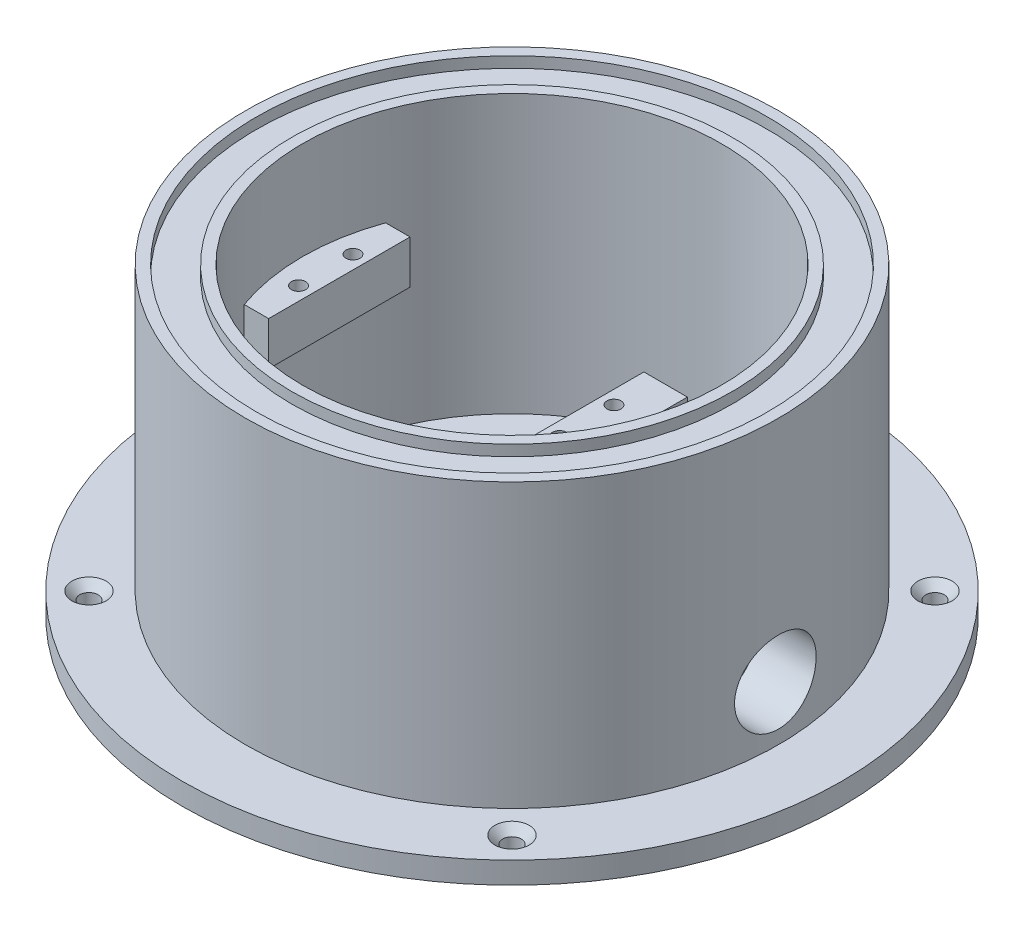
SolidWorks part; units mm, degrees
ref_plane "Front Plane" through (0, 0, 0) normal (0, 0, 1) x (1, 0, 0)
ref_plane "Top Plane" through (0, 0, 0) normal (0, 1, 0) x (1, 0, 0)
ref_plane "Right Plane" through (0, 0, 0) normal (1, 0, 0) x (0, 0, -1)
sketch "Sketch1" plane through (0, 0, 0) normal (0, 1, 0) x (1, 0, 0)
  circle A0 centre (0, 0) radius 60.625
  circle A1 centre (0, 0) radius 45
  dimension "D1" = 121.25
  dimension "D2" = 90
extrude "Boss-Extrude1" add sketch "Sketch1" along normal blind 4 contours A0
sketch "Sketch2" plane through (0, 4, 0) normal (0, 1, 0) x (1, 0, 0)
  circle A0 centre (0, 0) radius 45 construction
  circle A1 centre (0, 0) radius 45
  circle A2 centre (0, 0) radius 49
  dimension "D1" = 4
extrude "Boss-Extrude2" add sketch "Sketch2" along normal blind 52
ref_plane "Plane1" through (0, 36, 0) normal (0, 1, 0) x (1, 0, 0)
sketch "Sketch4" plane through (0, 0, 0) normal (0, 0, 1) x (1, 0, 0)
  line L0 (-60.625, 0) -> (60.625, 0) construction
  line L1 (11.25, 38) -> (19.25, 38)
  line L2 (11.25, 38) -> (11.25, 0)
  line L3 (11.25, 0) -> (19.25, 0)
  line L4 (19.25, 38) -> (19.25, 0)
  line L5 (49, 56) -> (-49, 56) construction
  line L6 (-45, 56) -> (-45, 4)
  line L7 (-31.75, 38) -> (-46.75, 38)
  line L8 (-31.75, 38) -> (-31.75, 30)
  line L9 (-31.75, 30) -> (-46.75, 30)
  line L10 (-46.75, 38) -> (-46.75, 30)
  line L11 (60.625, 4) -> (-60.625, 4) construction
  line L12 (-31.75, 30) -> (-45, 16.75)
  dimension "D1" = 11.25
  dimension "D2" = 8
  dimension "D3" = 18
  dimension "D4" = 43
  dimension "D5" = 15
  dimension "D6" = 8
  dimension "D7" = 45
  dimension "D8" = 18
extrude "Boss-Extrude4" add sketch "Sketch4" along normal mid plane 26 contours L9 L8 L7 L6 | L12 L9 L6 | L1 L4 L3 L2
sketch "Sketch5" plane through (0, 0, 0) normal (0, -1, 0) x (1, 0, 0)
  line L0 (11.25, 13) -> (29.0674, 34.3524)
  line L1 (11.25, -13) -> (29.0674, -34.3524)
  line L2 (11.25, 13) -> (11.25, -13)
  circle A0 centre (0, 0) radius 45 construction
  arc A1 (29.0674, -34.3524) -> (29.0674, 34.3524) centre (0, 0) ccw
extrude "Boss-Extrude5" add sketch "Sketch5" against normal up to surface (4 mm away) contours L0 A1 L1 L2 up to face at (0, 4, 60.625)
sketch "Sketch18" plane through (0, 56, 0) normal (0, 1, 0) x (1, 0, 0)
  circle A0 centre (0, 0) radius 38.5
  circle A1 centre (0, 0) radius 45.1137
extrude "Boss-Extrude6" add sketch "Sketch18" against normal up to surface (56 mm away) from offset 0 up to face at (0, 0, 60.625)
sketch "Sketch7" plane through (0, 38, 0) normal (0, 1, 0) x (1, 0, 0)
  line L0 (-31.75, -13) -> (-31.75, 13) construction
  circle A0 centre (-34.25, 5) radius 1.3
  circle A1 centre (-34.25, -5) radius 1.3
  circle A2 centre (13.75, 5) radius 1.3
  circle A3 centre (13.75, -5) radius 1.3
  dimension "D1" = 2.6
  dimension "D2" = 2.6
  dimension "D3" = 10
  dimension "D4" = 5
  dimension "D5" = 2.5
  dimension "D7" = 48
  dimension "D6" = 2
extrude "Cut-Extrude4" cut sketch "Sketch7" against normal blind 7.2
sketch "Sketch9" plane through (11.25, 0, 0) normal (-1, 0, 0) x (0, 0, 1)
  line L0 (13, 0) -> (-13, 0) construction
  line L1 (-5, 29) -> (5, 29)
  line L2 (-5, 29) -> (-5, 0)
  line L3 (-5, 0) -> (5, 0)
  line L4 (5, 29) -> (5, 0)
  line L5 (-5, 29) -> (5, 0) construction
  line L6 (-5, 0) -> (5, 29) construction
  line L7 (0, 0) -> (0, 29) construction
  line L8 (13, 38) -> (-13, 38) construction
  line L10 (5, 5) -> (-5, 5)
  point P0 (0, 14.5)
  dimension "D1" = 10
  dimension "D2" = 9
  dimension "D3" = 5
extrude "Cut-Extrude7" cut sketch "Sketch9" against normal up to surface (8 mm away) contours L10 L4 L1 L2 up to face at (19.25, 21, 0)
ref_plane "Plane2" through (49, 0, 0) normal (1, 0, 0) x (0, 0, -1)
sketch "Sketch11" plane through (49, 0, 0) normal (1, 0, 0) x (0, 0, -1)
  circle A0 centre (0, 14) radius 7.5
  dimension "D1" = 15
  dimension "D2" = 14
extrude "Cut-Extrude8" cut sketch "Sketch11" against normal blind 20
sketch "Sketch12" plane through (0, 4, 0) normal (0, 1, 0) x (1, 0, 0)
  line L5 (27.25, 13.6999) -> (27.25, -13.6999)
  line L6 (27.25, 13.6999) -> (27.25, -13.6999)
  line L9 (24.25, 16.0926) -> (24.25, -16.0926)
  line L10 (19.25, -13) -> (19.25, 13) construction
  arc A1 (27.25, -13.6999) -> (27.25, 13.6999) centre (0, 0) ccw
  arc A2 (27.25, -13.6999) -> (27.25, 13.6999) centre (0, 0) ccw
  dimension "D2" = 5
  dimension "D1" = 8
extrude "Cut-Extrude9" cut sketch "Sketch12" against normal through all
sketch "Sketch14" plane through (0, 4, 0) normal (0, 1, 0) x (1, 0, 0)
  circle A0 centre (-38.8909, 38.8909) radius 1.5
  circle A1 centre (38.8909, 38.8909) radius 1.5
  circle A2 centre (38.8909, -38.8909) radius 1.5
  circle A3 centre (-38.8909, -38.8909) radius 1.5
  point P15 (0, 0)
  dimension "D1" = 3
  dimension "D4" = 4
hole_wizard "CSK for M3 Countersunk Flat Head Screw1" positions "Sketch15" profile "Sketch17" countersink size "M3" standard "DIN" end condition up to next
sketch "Sketch15" plane through (0, 4, 0) normal (0, 1, 0) x (1, 0, 0)
  point P0 (-38.8909, 38.8909)
  point P3 (-38.8909, -38.8909)
  point P6 (38.8909, -38.8909)
  point P9 (38.8909, 38.8909)
sketch "Sketch17" plane through (-38.8909, 4, -38.8909) normal (1, 0, 0) x (0, 0, 1)
  line L0 (0, 0) -> (0, 4)
  line L1 (0, 4) -> (1.7, 4)
  line L2 (1.7, 4) -> (1.7, 1.45)
  line L3 (1.7, 1.45) -> (3.15, 0)
  line L5 (3.15, 0) -> (0, 0)
  line L6 (-1.7, 1.45) -> (-3.15, 0) construction
  line L11 (0, -6.35) -> (0, 107.95) construction
  dimension "Thru Hole Dia." = 3.4
  dimension "Thru Hole Depth" = 4
  dimension "Near C'Sink Dia." = 6.3
  dimension "Near C'Sink Angle" = 90
sketch "Sketch20" plane through (0, 5, 0) normal (0, 1, 0) x (1, 0, 0)
  circle A1 centre (0, 0) radius 38.7084
extrude "Boss-Extrude7" add sketch "Sketch20" against normal up to surface (5 mm away) up to face at (-38.8909, 0, -37.1909)
sketch "Sketch21" plane through (0, 56, 0) normal (0, 1, 0) x (1, 0, 0)
  circle A0 centre (0, 0) radius 47
  circle A1 centre (0, 0) radius 40.5
extrude "Cut-Extrude10" cut sketch "Sketch21" against normal blind 2
